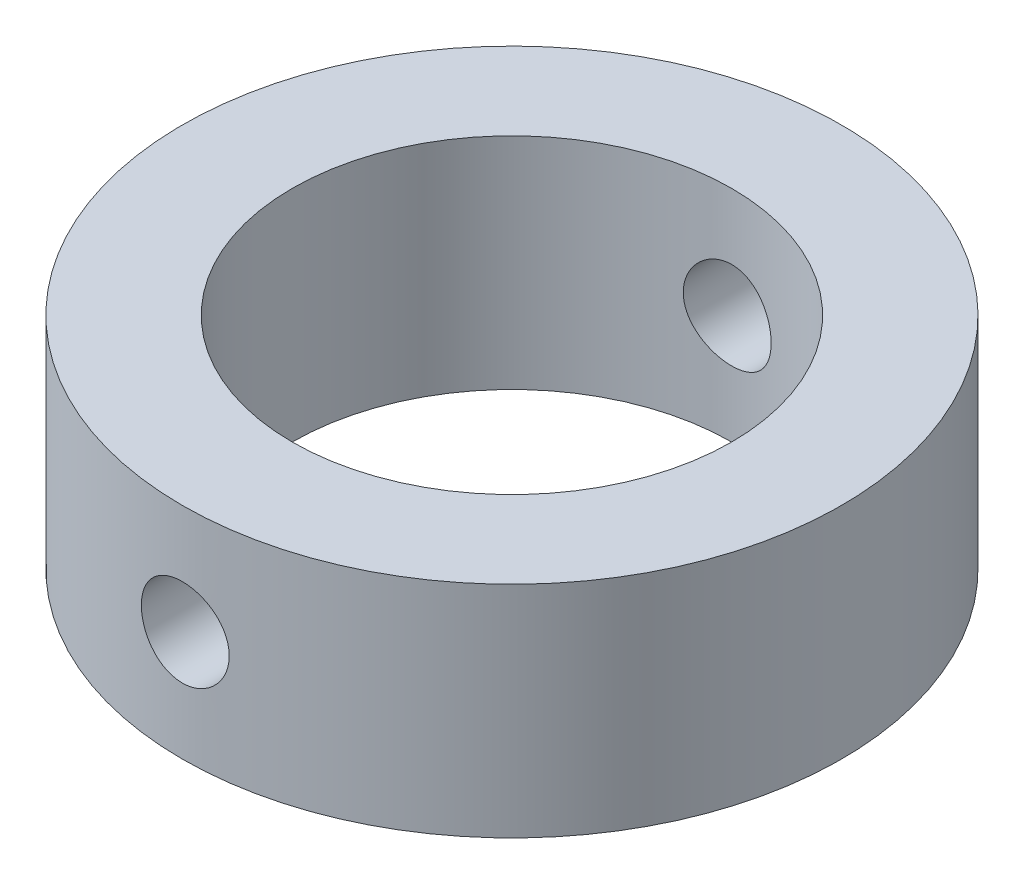
SolidWorks part; units mm, degrees
ref_plane "Front Plane" through (0, 0, 0) normal (0, 0, 1) x (1, 0, 0)
ref_plane "Top Plane" through (0, 0, 0) normal (0, 1, 0) x (1, 0, 0)
ref_plane "Right Plane" through (0, 0, 0) normal (1, 0, 0) x (0, 0, -1)
sketch "Croquis1" plane through (0, 0, 0) normal (0, 1, 0) x (1, 0, 0)
  circle A0 centre (0, 0) radius 22.5
  circle A1 centre (0, 0) radius 15
  dimension "D1" = 45
  dimension "D2" = 30
extrude "Saliente-Extruir1" add sketch "Croquis1" along normal blind 15
sketch "Croquis2" plane through (0, 0, 0) normal (0, 0, 1) x (1, 0, 0)
  circle A0 centre (0, 7.5) radius 3
  dimension "D1" = 6
  dimension "D2" = 7.5
extrude "Cortar-Extruir1" cut sketch "Croquis2" against normal mid plane 60
